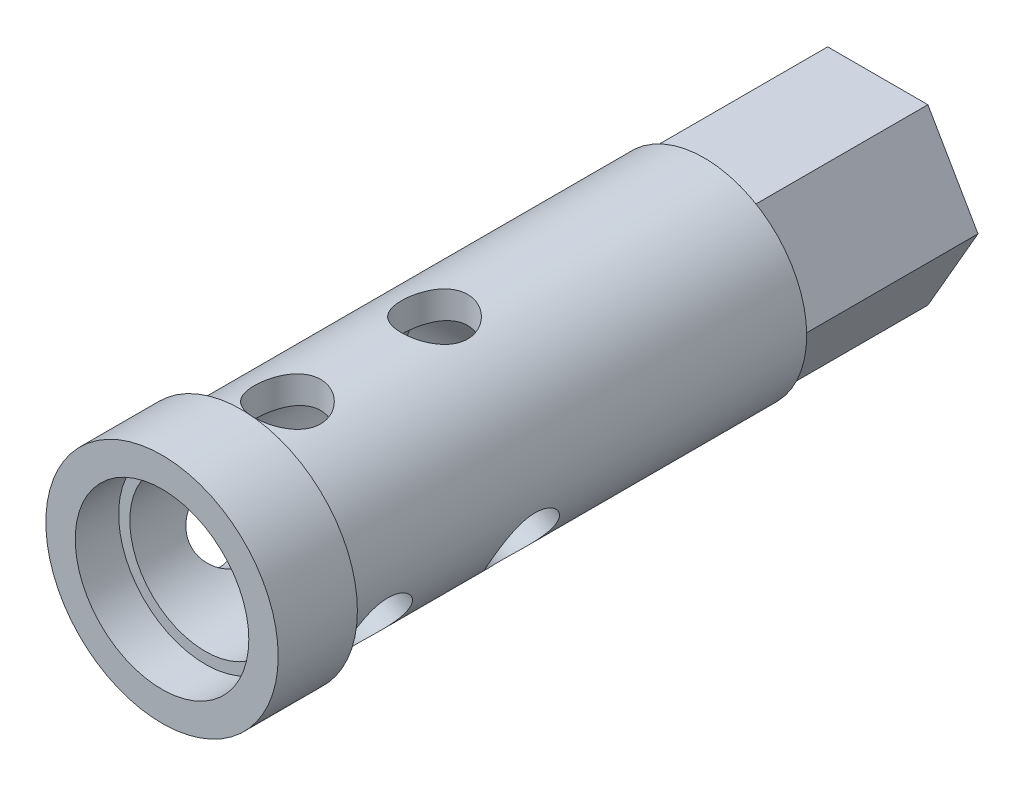
SolidWorks part; units mm, degrees
material "7075-T6 (SN)"
ref_plane "Front Plane" through (0, 0, 0) normal (0, 0, 1) x (1, 0, 0)
ref_plane "Top Plane" through (0, 0, 0) normal (0, 1, 0) x (1, 0, 0)
ref_plane "Right Plane" through (0, 0, 0) normal (1, 0, 0) x (0, 0, -1)
sketch "Sketch1" plane through (0, 0, 0) normal (1, 0, 0) x (0, 0, -1)
  line L0 (0, 0) -> (0, 2.7375) construction
  line L1 (0, 6.35) -> (3.175, 6.35)
  line L2 (3.175, 6.35) -> (3.175, 5.5315)
  line L3 (5.7937, 8.5) -> (5.7937, 13) construction
  line L4 (5.7937, 13) -> (0.7938, 13) construction
  line L5 (0.7938, 13) -> (0.7938, 8.5) construction
  line L6 (5.7937, 13) -> (5.7937, 14) construction
  line L7 (5.7937, 14) -> (6.7937, 14) construction
  line L8 (6.7937, 14) -> (6.7937, 7.5) construction
  line L9 (0, 8.5) -> (5.7937, 8.5)
  line L10 (0, 8.5) -> (0, 6.35)
  line L11 (5.7937, 8.5) -> (5.7937, 7.5)
  line L12 (5.7937, 7.5) -> (39.6687, 7.5)
  line L13 (6.7937, 14) -> (6.7937, 20.32) construction
  line L14 (6.7937, 20.32) -> (16.3187, 20.32) construction
  line L15 (16.3187, 20.32) -> (16.3187, 7.5) construction
  line L16 (11.5562, 19.5) -> (11.5562, 7.5) construction
  line L17 (11.5562, 19.5) -> (16.5562, 19.5) construction
  line L18 (16.5562, 19.5) -> (16.5562, 7.5) construction
  line L19 (9.175, 20.32) -> (9.175, 0) construction
  line L20 (16.5562, 19.5) -> (16.5562, 14) construction
  line L21 (16.5562, 14) -> (17.5562, 14) construction
  line L22 (17.5562, 14) -> (17.5562, 7.5) construction
  line L23 (0, 0) -> (31.9294, 0)
  line L24 (17.5562, 14) -> (17.5562, 26.67) construction
  line L25 (17.5562, 26.67) -> (27.0812, 26.67) construction
  line L26 (27.0812, 26.67) -> (27.0812, 7.5) construction
  line L27 (22.3187, 7.5) -> (22.3187, 19.5) construction
  line L28 (22.3187, 19.5) -> (27.3187, 19.5) construction
  line L29 (27.3187, 19.5) -> (27.3187, 7.5) construction
  line L30 (19.9375, 26.67) -> (19.9375, 0) construction
  line L31 (27.3187, 19.5) -> (27.3187, 14) construction
  line L32 (27.3187, 14) -> (28.3187, 14) construction
  line L33 (28.3187, 14) -> (28.3187, 7.5) construction
  line L34 (28.3187, 19.5) -> (33.3187, 19.5) construction
  line L35 (33.3187, 19.5) -> (33.3187, 7.5) construction
  line L36 (33.3187, 2.3813) -> (33.3187, 38.6538) construction
  line L37 (26.9687, 0) -> (26.9687, 30.1625) construction
  line L38 (28.5562, 30.1625) -> (28.5562, 0) construction
  line L39 (0, 0) -> (0, 2.7375) construction
  line L40 (6.35, 42.8625) -> (6.35, 0) construction
  line L41 (4.7625, 50.8) -> (4.7625, 0) construction
  line L42 (-17.4625, 46.0375) -> (-17.4625, 53.5375)
  line L43 (3.175, 5.5315) -> (23.1125, 5.5315)
  line L44 (0, 4.7378) -> (13.0644, 4.7378) construction
  line L45 (0, 2.7375) -> (14.0479, 2.7375)
  line L46 (11.9076, 4.7378) -> (9.9073, 2.7375) construction
  line L47 (17.2049, 4.7378) -> (19.2052, 2.7375) construction
  line L48 (21.1281, 4.7378) -> (23.1284, 2.7375)
  line L49 (16.0481, 4.7378) -> (16.0481, 0) construction
  line L50 (7.9844, 4.7378) -> (5.9841, 2.7375) construction
  line L51 (13.0644, 4.7378) -> (15.0646, 2.7375) construction
  line L52 (16.0481, 4.7378) -> (14.0479, 2.7375)
  line L53 (29.1919, 2.7375) -> (31.9294, 0)
  line L54 (16.0481, 4.7378) -> (21.1281, 4.7378)
  line L55 (39.6687, 2.3813) -> (39.6687, 7.5)
  line L56 (0, 6.35) -> (0, 44.45) construction
  line L57 (23.1284, 2.7375) -> (29.1919, 2.7375)
  line L58 (23.1125, 5.5315) -> (24.5284, 3.175)
  line L59 (24.5284, 3.175) -> (29.8649, 3.175)
  line L60 (29.8649, 3.175) -> (30.3419, 2.3813)
  line L61 (30.3419, 2.3813) -> (39.6687, 2.3813)
  line L62 (30.3419, 2.3813) -> (29.5481, 2.3813)
  line L63 (0, 2.7375) -> (-3.175, 2.7375)
  line L64 (-3.175, 2.7375) -> (-3.175, 2)
  line L65 (-3.175, 2) -> (-9.9531, 2)
  line L66 (-9.9531, 2) -> (-9.9531, 0)
  line L67 (-9.9531, 0) -> (0, 0)
  line L68 (-3.175, 2.7375) -> (-3.175, 4.5)
  line L69 (-3.175, 4.5) -> (-7.175, 4.5)
  line L70 (-7.175, 4.5) -> (-7.175, 2)
  line L71 (-3.175, 3.5) -> (-1.5875, 3.5)
  line L72 (-1.5875, 3.5) -> (-1.5875, 8.5)
  line L73 (-1.5875, 8.5) -> (-13.9219, 8.5)
  line L74 (-12.3344, 3.429) -> (-12.3344, 3.81)
  line L75 (-12.3344, 3.81) -> (-7.175, 3.81)
  line L76 (-7.302, 0) -> (-7.302, 3.175)
  line L77 (-7.302, 3.175) -> (-8.8895, 3.175)
  line L78 (-8.8895, 3.175) -> (-8.8895, 0)
  line L79 (-10.35, 0) -> (-10.35, 3.429)
  line L80 (-10.35, 3.429) -> (-12.3344, 3.429)
  line L81 (-12.3344, 3.429) -> (-12.3344, 0)
  line L82 (-12.3344, 0) -> (-10.35, 0)
  line L83 (-7.175, 4.5) -> (-7.175, 6.985)
  line L84 (-7.175, 6.985) -> (-13.9219, 6.985)
  line L85 (-13.9219, 6.985) -> (-13.9219, 8.5)
  line L86 (-13.9219, 2.0828) -> (-13.9219, 6.985)
  line L87 (-12.3344, 2.0828) -> (-13.9219, 2.0828)
  circle A0 centre (-17.4625, 46.0375) radius 7.5
  circle A1 centre (-17.4625, 46.0375) radius 5.5315
  circle A2 centre (-17.4625, 53.1565) radius 2.3812
  circle A3 centre (-17.4625, 51.1562) radius 2.3812
  circle A4 centre (-17.4625, 46.0375) radius 12.7
  arc A5 (-14.9548, 53.1058) -> (-19.9702, 53.1058) centre (-17.4625, 53.1565) ccw
  circle A6 centre (-17.4625, 46.0375) radius 2.7375
  circle A7 centre (-17.4625, 46.0375) radius 4.7378
  circle A8 centre (-17.4625, 46.0375) radius 7.754
  circle A9 centre (9.175, 7.119) radius 2.3813 construction
  circle A10 centre (9.175, 5.3727) radius 2.3813 construction
  circle A11 centre (9.175, 5.1187) radius 2.3813 construction
  circle A12 centre (19.9375, 7.119) radius 2.3813 construction
  circle A13 centre (19.9375, 5.3727) radius 2.3813 construction
  circle A14 centre (19.9375, 5.1187) radius 2.3813 construction
  dimension "D24" = 15
  dimension "D25" = 4.7625
  dimension "D27" = 25.4
  dimension "D28" = 5.0165
  dimension "D29" = 0.7937
  dimension "D30" = 0.254
  dimension "D31" = 11.063
  dimension "D32" = 5.475
  dimension "D34" = 9.4755
  dimension "D37" = 4.7625
  dimension "D39" = 2.1273
  dimension "D1" = 8.5
  dimension "D2" = 3.175
  dimension "D3" = 6.35
  dimension "D4" = 5.7937
  dimension "D5" = 7.5
  dimension "D6" = 5
  dimension "D7" = 13
  dimension "D8" = 1
  dimension "D9" = 14
  dimension "D10" = 9.525
  dimension "D11" = 20.32
  dimension "D12" = 4.7625
  dimension "D13" = 5
  dimension "D14" = 2.3813
  dimension "D15" = 12
  dimension "D16" = 26.67
  dimension "D17" = 4.7625
  dimension "D18" = 2.3813
  dimension "D19" = 6.35
  dimension "D20" = 1.5875
  dimension "D21" = 6.35
  dimension "D22" = 1.5875
  dimension "D23" = 6.35
  dimension "D26" = 0.381
  dimension "D33" = 5.5315
  dimension "D35" = 4.7378
  dimension "D36" = 2.7375
  dimension "D38" = 0.381
  dimension "D40" = 45
  dimension "D41" = 5.2973
  dimension "D42" = 10.7625
  dimension "D43" = 1.1906
  dimension "D44" = 5.08
  dimension "D45" = 1.1906
  dimension "D46" = 8.0637
  dimension "D47" = 5.08
  dimension "D48" = 6.0635
  dimension "D49" = 45
  dimension "D50" = 6.0635
  dimension "D51" = 0.7937
  dimension "D52" = 59
  dimension "D53" = 3.175
  dimension "D54" = 0.7937
  dimension "D55" = 2.3813
  dimension "D56" = 2
  dimension "D57" = 4.5
  dimension "D58" = 4
  dimension "D59" = 1.5875
  dimension "D60" = 4.69
  dimension "D61" = 1.5875
  dimension "D62" = 1.9844
  dimension "D63" = 3.429
  dimension "D64" = 2.7781
  dimension "D65" = 1.5875
  dimension "D66" = 3.175
  dimension "D67" = 0.127
  dimension "D68" = 0.3969
  dimension "D69" = 1.5875
  dimension "D70" = 3.81
  dimension "D71" = 3.175
  dimension "D72" = 2.0828
  dimension "D73" = 12.3344
  dimension "D74" = 1
revolve "Revolve1" add sketch "Sketch1" angle 360 about L23
sketch "Sketch2" plane through (0, 0, -39.6687) normal (0, 0, -1) x (-1, 0, 0)
  line L1 (7.3323, 0) -> (3.6662, 6.35)
  line L2 (3.6662, 6.35) -> (-3.6662, 6.35)
  line L3 (-3.6662, 6.35) -> (-7.3323, 0)
  line L4 (-7.3323, 0) -> (-3.6662, -6.35)
  line L5 (-3.6662, -6.35) -> (3.6662, -6.35)
  line L6 (3.6662, -6.35) -> (7.3323, 0)
  circle A0 centre (0, 0) radius 6.35 construction
  dimension "D1" = 12.7
extrude "Boss-Extrude1" add sketch "Sketch2" along normal blind 12.7
hole_wizard "1/4-20 Tapped Hole1" positions "Sketch4" profile "Sketch3" tap size "1/4-20" standard "ANSI Inch"
sketch "Sketch4" plane through (0, 0, -39.6687) normal (0, 0, 1) x (1, 0, 0)
  point P0 (0, 0)
sketch "Sketch3" plane through (0, 0, -39.6687) normal (1, 0, 0) x (0, -1, 0)
  line L0 (0, 0) -> (0, 12.7)
  line L1 (0, 12.7) -> (2.5527, 12.7)
  line L2 (2.5527, 12.7) -> (2.5527, 0)
  line L5 (2.5527, 0) -> (0, 0)
  line L11 (0, -6.35) -> (0, 107.95) construction
  dimension "Thru Tap Drill Dia." = 5.1054
  dimension "Thru Tap Drill Depth" = 12.7
cosmetic thread "Hole Thread1" parameters "D2"=6.35
ref_plane "Plane1" through (0, 7.5, 0) normal (0, 1, 0) x (1, 0, 0)
sketch "Sketch9" plane through (0, 7.5, 0) normal (0, 1, 0) x (1, 0, 0)
  point P0 (0, 9.175)
  point P2 (0, 19.9375)
hole_wizard "#11 (0.191) Diameter Hole2" positions "Sketch11" profile "Sketch12" hole size "#11" standard "ANSI Inch"
sketch "Sketch11" plane through (0, 7.5, 0) normal (0, 1, 0) x (1, 0, 0)
  point P0 (0, 9.175)
  point P3 (0, 19.9375)
sketch "Sketch12" plane through (0, 7.5, -9.175) normal (1, 0, 0) x (0, 0, 1)
  line L0 (0, 0) -> (0, 8.9565)
  line L1 (0, 8.9565) -> (2.4257, 7.499)
  line L2 (2.4257, 7.499) -> (2.4257, 0)
  line L5 (2.4257, 0) -> (0, 0)
  line L10 (0, 8.9565) -> (-2.4257, 7.499) construction
  line L11 (0, -6.35) -> (0, 107.95) construction
  dimension "Hole Dia." = 4.8514
  dimension "Hole Depth" = 7.499
  dimension "Drill Angle" = 118
pattern_circular "CirPattern1" count 3 every 120 about axis through (0, 0, 0) along (0, 0, 1) of "#11 (0.191) Diameter Hole2"
ref_plane "Plane2" through (0, 0, -21.1281) normal (0, 0, 1) x (1, 0, 0)
ref_plane "Plane3" through (0, 0, -13.0644) normal (0, 0, 1) x (1, 0, 0)
equation "\"D1@Sketch1\"=(17mm/2)"
equation "\"D5@Sketch1\"=15mm/2"
equation "\"D4@Sketch1\"=5mm+1/32"
equation "\"D6@Sketch1\"=5mm"
equation "\"D7@Sketch1\"=26mm/2"
equation "\"D8@Sketch1\"=1mm"
equation "\"D9@Sketch1\"=28mm/2"
equation "\"D11@Sketch1\"=(34-2)/20/2"
equation "\"D13@Sketch1\"=5mm"
equation "\"D15@Sketch1\"=24mm/2"
equation "\"D16@Sketch1\"=(44-2)/20/2"
equation "\"D33@Sketch1\"=\"D31@Sketch1\"/2"
equation "\"D35@Sketch1\"= \"D34@Sketch1\" / 2"
equation "\"D36@Sketch1\"= \"D32@Sketch1\" / 2"
equation "\"D39@Sketch1\" = \"D37@Sketch1\"/2-.01"
equation "\"D45@Sketch1\" = 3 / 64"
equation "\"D43@Sketch1\" = \"D45@Sketch1\""
equation "\"D47@Sketch1\"=\"D44@Sketch1\""
equation "\"D56@Sketch1\"=2mm"
equation "\"D57@Sketch1\"=9mm/2"
equation "\"D58@Sketch1\"=4mm"
equation "\"D63@Sketch1\"=.27/2"
equation "\"D64@Sketch1\"=1/16+3/64"
equation "\"D74@Sketch1\"=1mm"
